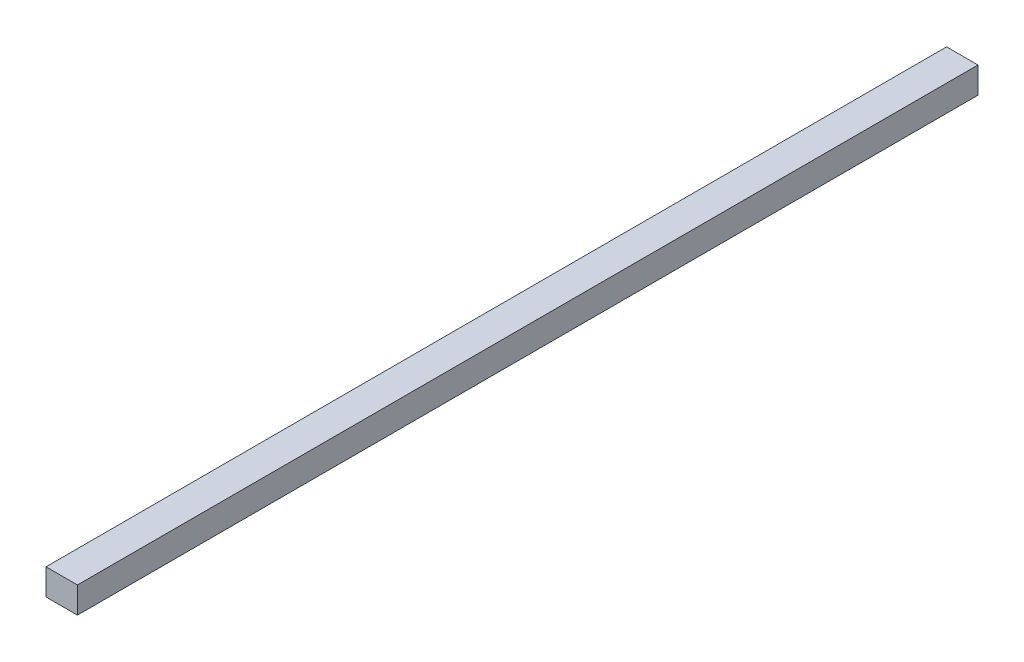
SolidWorks part; units mm, degrees
material "1060 Сплав"
ref_plane "Front" through (0, 0, 0) normal (0, 0, 1) x (1, 0, 0)
ref_plane "Top" through (0, 0, 0) normal (0, 1, 0) x (1, 0, 0)
ref_plane "Right" through (0, 0, 0) normal (1, 0, 0) x (0, 0, -1)
sketch "Эскиз1" plane through (0, 0, 0) normal (0, 0, 1) x (1, 0, 0)
  line L1 (0, 0) -> (12, 0)
  line L2 (0, 0) -> (0, 10)
  line L3 (0, 10) -> (12, 10)
  line L4 (12, 0) -> (12, 10)
  dimension "D1" = 10
  dimension "D2" = 12
extrude "Бобышка-Вытянуть1" add sketch "Эскиз1" along normal blind 344
